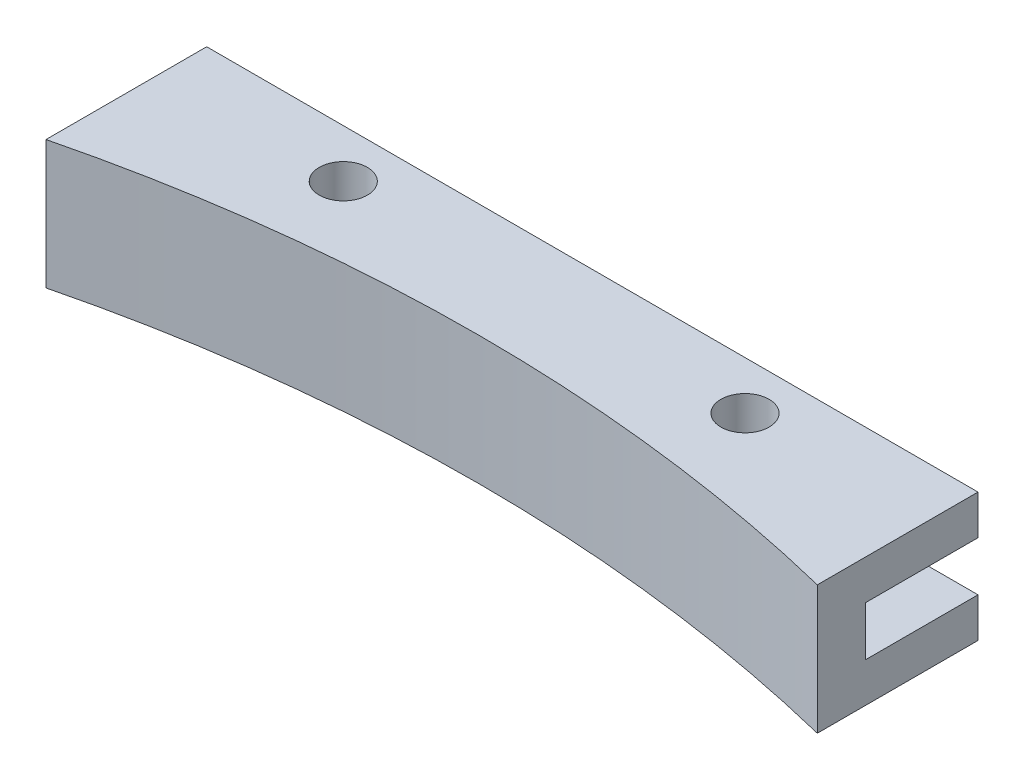
SolidWorks part; units mm, degrees
material "6061-T6 (SS)"
ref_plane "Front Plane" through (0, 0, 0) normal (0, 0, 1) x (1, 0, 0)
ref_plane "Top Plane" through (0, 0, 0) normal (0, 1, 0) x (1, 0, 0)
ref_plane "Right Plane" through (0, 0, 0) normal (1, 0, 0) x (0, 0, -1)
sketch "Sketch1" plane through (0, 0, 0) normal (0, 1, 0) x (1, 0, 0)
  line L0 (-20, 0) -> (0, 0)
  line L1 (24, -8) -> (24, -16.9227)
  line L2 (-24, -8) -> (-24, -16.9227)
  line L3 (-24, -14) -> (24, -14) construction
  line L4 (-20, 0) -> (-20, -8)
  line L5 (-20, -8) -> (-24, -8)
  line L6 (20, 0) -> (20, -8)
  line L7 (20, -8) -> (24, -8)
  line L22 (0, 0) -> (20, 0)
  line L25 (-24, -16.9227) -> (0, -114) construction
  line L26 (0, -114) -> (24, -16.9227) construction
  arc A0 (-24, -16.9227) -> (24, -16.9227) centre (0, -114) cw
  dimension "D1" = 6
  dimension "D2" = 100
  dimension "D3" = 8
  dimension "D4" = 20
  dimension "D5" = 48
extrude "Boss-Extrude1" add sketch "Sketch1" along normal mid plane 8
sketch "Sketch10" plane through (0, 4, 0) normal (0, 1, 0) x (1, 0, 0)
  line L0 (-20, -9.9227) -> (20, -9.9227) construction
  line L3 (-26.6292, -6.9227) -> (25.3174, -6.9227) construction
  line L4 (-26.6292, -14) -> (25.3174, -14) construction
  line L5 (0, 0) -> (0, -20.7484) construction
  line L6 (-20, 0) -> (-20, -8) construction
  line L7 (20, -8) -> (20, 0) construction
  line L8 (24, -16.9227) -> (24, -8) construction
  line L9 (-24, -8) -> (24, -8)
  line L10 (-24, -8) -> (-24, -6.9227)
  line L11 (-24, -6.9227) -> (24, -6.9227)
  line L12 (24, -8) -> (24, -6.9227)
  line L13 (20, 0) -> (-20, 0) construction
  line L14 (-24, -6.9227) -> (24, -6.9227)
  line L15 (-24, -6.9227) -> (-24, 0)
  line L16 (-24, 0) -> (24, 0)
  line L17 (24, -6.9227) -> (24, 0)
  circle A0 centre (-12.5, -9.9227) radius 1.5
  circle A1 centre (12.5, -9.9227) radius 1.5
  arc A2 (24, -16.9227) -> (-24, -16.9227) centre (0, -114) ccw construction
  line M14 (20, 0) -> (-20, 0)
  line M15 (-20, 0) -> (-20, -8)
  line M17 (20, -8) -> (20, 0)
  dimension "D1" = 3
  dimension "D2" = 12.5
  dimension "D4" = 10
  dimension "D5" = 3
extrude "Cut-Extrude2" cut sketch "Sketch10" against normal through all contours A0 | A1 | L11 M15 M17 M14
sketch "Sketch11" plane through (0, 4, 0) normal (0, 1, 0) x (1, 0, 0)
  line L0 (24, -16.9227) -> (24, -8) construction
  line L1 (-24, -8) -> (24, -8)
  line L2 (-24, -8) -> (-24, -6.9227)
  line L3 (-24, -6.9227) -> (24, -6.9227)
  line L4 (24, -8) -> (24, -6.9227)
  line L5 (-20, -6.9227) -> (20, -6.9227) construction
extrude "Boss-Extrude2" add sketch "Sketch11" against normal up to surface (8 mm away) up to face at (0, -4, 9.596)
sketch "Sketch12" plane through (-24, 0, 0) normal (-1, 0, 0) x (0, 0, 1)
  line L0 (6.9227, -4) -> (6.9227, 4) construction
  line L1 (6.9227, -1.5375) -> (13.9227, -1.5375)
  line L2 (6.9227, -1.5375) -> (6.9227, 1.5375)
  line L3 (6.9227, 1.5375) -> (13.9227, 1.5375)
  line L4 (13.9227, -1.5375) -> (13.9227, 1.5375)
  line L5 (6.9227, 0) -> (16.9227, 0) construction
  line L6 (16.9227, 4) -> (16.9227, -4) construction
  line L7 (9.9227, 4) -> (9.9227, -4) construction
  line L8 (6.9227, 4) -> (16.9227, 4) construction
  line L9 (6.9227, -4) -> (16.9227, -4) construction
  dimension "D1" = 3
  dimension "D2" = 3.075
  dimension "D3" = 4
extrude "Cut-Extrude3" cut sketch "Sketch12" against normal through all
